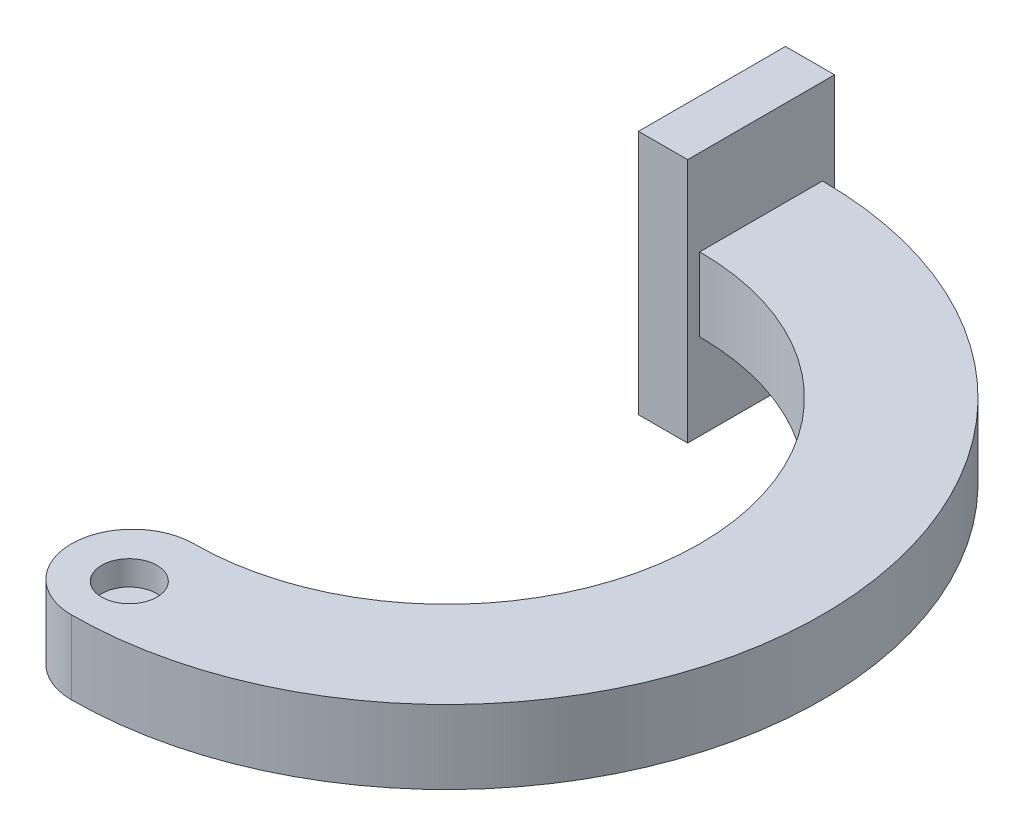
SolidWorks part; units mm, degrees
ref_plane "Front Plane" through (0, 0, 0) normal (0, 0, 1) x (1, 0, 0)
ref_plane "Top Plane" through (0, 0, 0) normal (0, 1, 0) x (1, 0, 0)
ref_plane "Right Plane" through (0, 0, 0) normal (1, 0, 0) x (0, 0, -1)
sketch "Sketch1" plane through (0, 0, 0) normal (0, 1, 0) x (1, 0, 0)
  line L0 (0, 0) -> (0, 51.2) construction
  line L3 (0, 61.2) -> (0, 79.6265) construction
  line L4 (0, 61.2) -> (0, 51.2)
  arc A0 (0, 0) -> (0, 61.2) centre (0, 30.6) ccw
  arc A1 (0, 10) -> (0, 51.2) centre (0, 30.6) ccw
  arc A3 (0, 10) -> (0, 0) centre (0, 5) ccw
  dimension "D1" = 20.6
  dimension "D2" = 30.6
  dimension "D3" = 10
  dimension "D4" = 10
extrude "Boss-Extrude1" add sketch "Sketch1" along normal mid plane 6
sketch "Sketch2" plane through (0, 3, 0) normal (0, 1, 0) x (1, 0, 0)
  circle A0 centre (0, 4.7275) radius 2.25
  dimension "D1" = 4.5
extrude "Cut-Extrude1" cut sketch "Sketch2" against normal blind 2
sketch "Sketch4" plane through (0, 0, 0) normal (-1, 0, 0) x (0, 0, 1)
  line L0 (-61.2, 3) -> (-61.2, -3) construction
  line L1 (-62.1861, -10) -> (-50.2139, -10)
  line L2 (-62.1861, -10) -> (-62.1861, 10)
  line L3 (-62.1861, 10) -> (-50.2139, 10)
  line L4 (-50.2139, -10) -> (-50.2139, 10)
  line L5 (-56.2, 10) -> (-56.2, -10) construction
  line L6 (-62.1861, 0) -> (-50.2139, 0) construction
  line L7 (-51.2, 3) -> (-51.2, -3) construction
  point P0 (-56.2, 0)
  dimension "D1" = 20
extrude "Boss-Extrude3" add sketch "Sketch4" along normal blind 4
